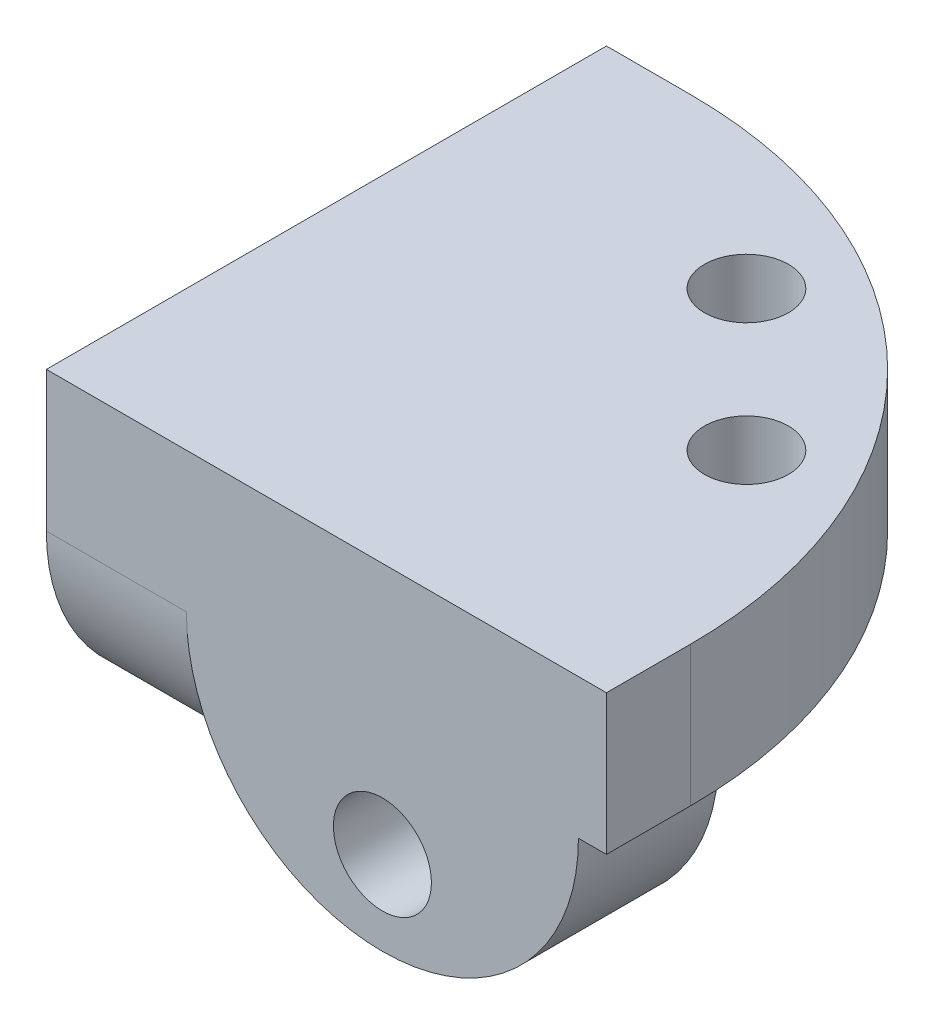
SolidWorks part; units mm, degrees
ref_plane "Front Plane" through (0, 0, 0) normal (0, 0, 1) x (1, 0, 0)
ref_plane "Top Plane" through (0, 0, 0) normal (0, 1, 0) x (1, 0, 0)
ref_plane "Right Plane" through (0, 0, 0) normal (1, 0, 0) x (0, 0, -1)
sketch "Sketch1" plane through (0, 0, 0) normal (0, 1, 0) x (1, 0, 0)
  line L0 (0, 15) -> (20, 15) construction
  line L1 (0, 0) -> (20, 0)
  line L2 (0, 0) -> (0, 20)
  line L3 (0, 20) -> (20, 20)
  line L4 (20, 0) -> (20, 20)
  line L5 (15, 20) -> (15, 0) construction
  line L6 (0, 15) -> (10, 15) construction
  line L7 (15, 0) -> (15, 10) construction
  circle A0 centre (10, 15) radius 1.5
  circle A1 centre (15, 10) radius 1.5
  dimension "D1" = 20
  dimension "D2" = 15
  dimension "D3" = 15
extrude "Boss-Extrude1" add sketch "Sketch1" along normal blind 5
sketch "Sketch2" plane through (0, 0, 0) normal (0, 0, 1) x (1, 0, 0)
  line L0 (0, 0) -> (20, 0) construction
  line L1 (19, 0) -> (5, 0)
  line L2 (12, 0) -> (12, -7) construction
  arc A0 (5, 0) -> (19, 0) centre (12, 0) ccw
  circle A1 centre (12, -4) radius 1.75
  dimension "D1" = 5
  dimension "D3" = 4
  dimension "D2" = 14
extrude "Boss-Extrude2" add sketch "Sketch2" against normal blind 5
sketch "Sketch3" plane through (0, 0, 0) normal (-1, 0, 0) x (0, 0, 1)
  line L0 (-20, 0) -> (0, 0) construction
  line L1 (0, 0) -> (-14, 0)
  line L2 (-7, 0) -> (-7, -7) construction
  arc A0 (0, 0) -> (-14, 0) centre (-7, 0) cw
  circle A1 centre (-7, -4) radius 1.75
  dimension "D1" = 0
  dimension "D3" = 4
  dimension "D4" = 3.5
  dimension "D2" = 14
extrude "Boss-Extrude3" add sketch "Sketch3" against normal blind 5
fillet "Fillet1" radius 17
